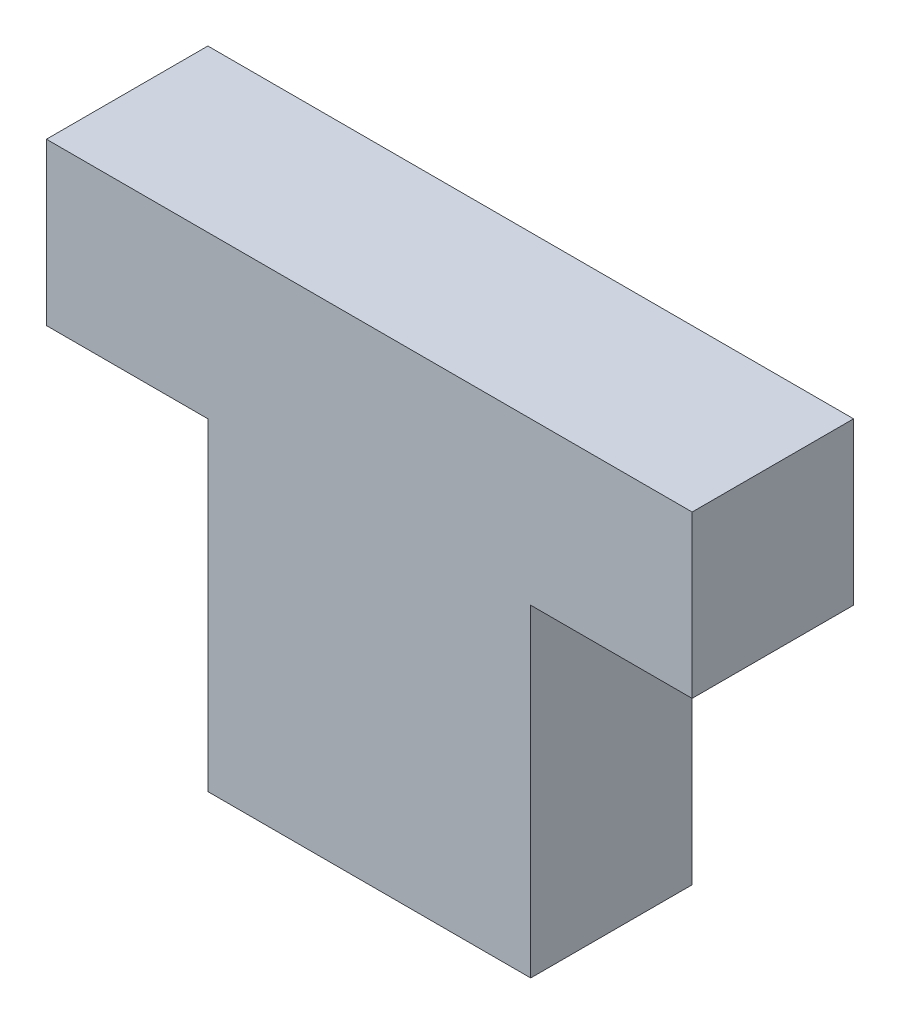
SolidWorks part; units mm, degrees
ref_plane "Front Plane" through (0, 0, 0) normal (0, 0, 1) x (1, 0, 0)
ref_plane "Top Plane" through (0, 0, 0) normal (0, 1, 0) x (1, 0, 0)
ref_plane "Right Plane" through (0, 0, 0) normal (1, 0, 0) x (0, 0, -1)
sketch "Sketch1" plane through (0, 0, 0) normal (0, 0, 1) x (1, 0, 0)
  line L1 (0, 0) -> (-10, 0)
  line L2 (0, 0) -> (0, -10)
  line L3 (0, -10) -> (-10, -10)
  line L4 (-10, 0) -> (-10, -10)
  line L5 (-15, 0) -> (5, 0)
  line L6 (-15, 0) -> (-15, 5)
  line L7 (-15, 5) -> (5, 5)
  line L8 (5, 0) -> (5, 5)
  point P9 (-5, 5)
  point P10 (-5, -10)
  dimension "D1" = 10
  dimension "D2" = 10
  dimension "D3" = 20
  dimension "D4" = 5
extrude "Boss-Extrude1" add sketch "Sketch1" along normal blind 5 contours L1 L4 L3 L2 | L5 L8 L7 L6 L1
